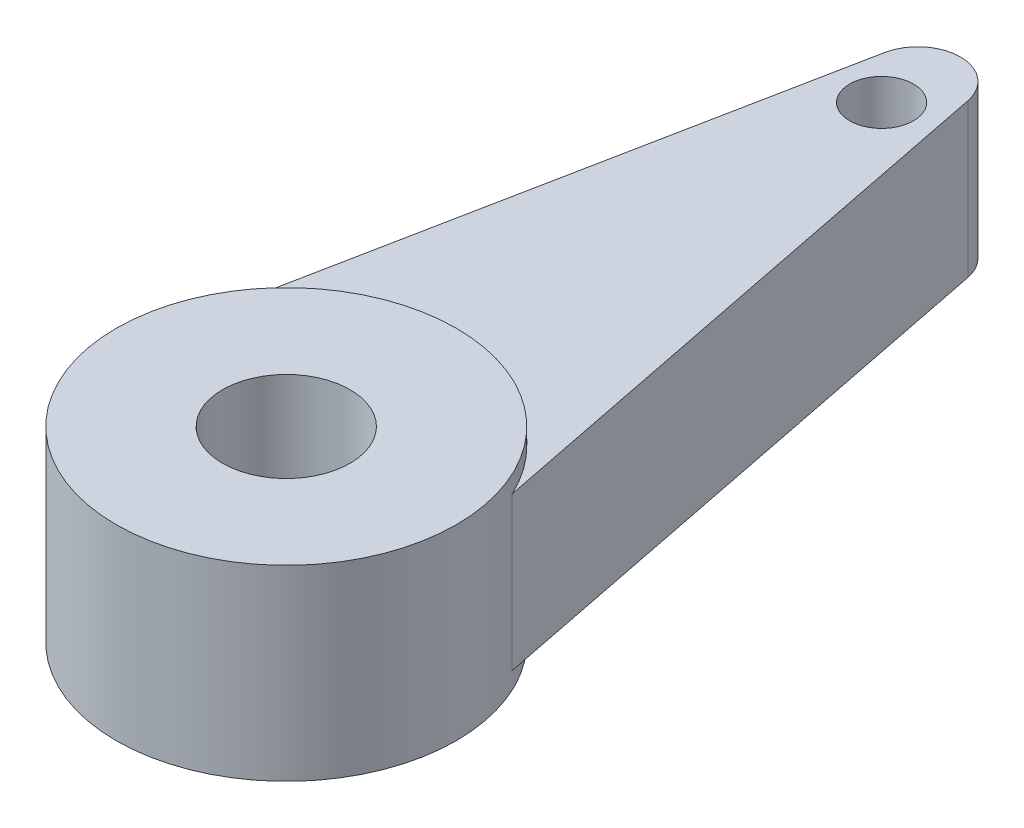
SolidWorks part; units mm, degrees
ref_plane "Front Plane" through (0, 0, 0) normal (0, 0, 1) x (1, 0, 0)
ref_plane "Top Plane" through (0, 0, 0) normal (0, 1, 0) x (1, 0, 0)
ref_plane "Right Plane" through (0, 0, 0) normal (1, 0, 0) x (0, 0, -1)
sketch "Sketch1" plane through (0, 0, 0) normal (0, 1, 0) x (1, 0, 0)
  circle A0 centre (0, 0) radius 50.8
  circle A1 centre (0, 0) radius 19.05
  dimension "D1" = 101.6
  dimension "D2" = 38.1
extrude "Boss-Extrude1" add sketch "Sketch1" along normal mid plane 55.88
sketch "Sketch3" plane through (0, 0, 0) normal (0, 1, 0) x (1, 0, 0)
  line L0 (-46.0705, 21.4044) -> (46.0705, 21.4044)
  line L1 (46.0705, 21.4044) -> (0, 254)
  line L2 (0, 254) -> (-46.0705, 21.4044)
  circle A0 centre (0, 0) radius 50.8 construction
  circle A1 centre (0, 177.8) radius 9.525
  dimension "D1" = 19.05
extrude "Boss-Extrude3" add sketch "Sketch3" along normal mid plane 45.72
fillet "Fillet1" radius 12.7 1 edges at (0, 0, -254)
